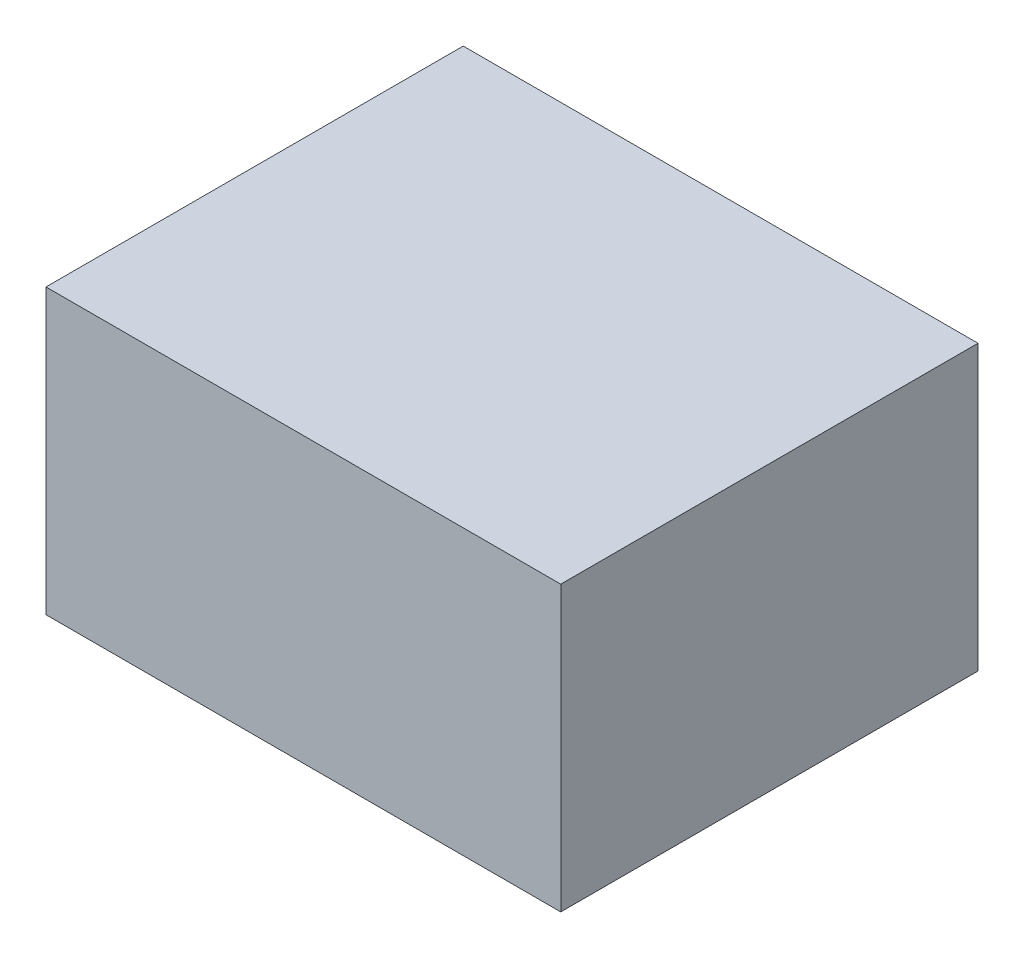
SolidWorks part; units mm, degrees
material "leadbattery"
ref_plane "Front" through (0, 0, 0) normal (0, 0, 1) x (1, 0, 0)
ref_plane "Top" through (0, 0, 0) normal (0, 1, 0) x (1, 0, 0)
ref_plane "Right" through (0, 0, 0) normal (1, 0, 0) x (0, 0, -1)
sketch "Sketch1" plane through (0, 0, 0) normal (0, 1, 0) x (1, 0, 0)
  line L1 (172.72, 140) -> (-172.72, 140)
  line L2 (172.72, 140) -> (172.72, -140)
  line L3 (172.72, -140) -> (-172.72, -140)
  line L4 (-172.72, 140) -> (-172.72, -140)
  line L5 (172.72, 140) -> (-172.72, -140) construction
  line L6 (172.72, -140) -> (-172.72, 140) construction
  point P0 (0, 0)
  dimension "D1" = 345.44
  dimension "D2" = 280
extrude "Boss-Extrude1" add sketch "Sketch1" along normal blind 190.5
